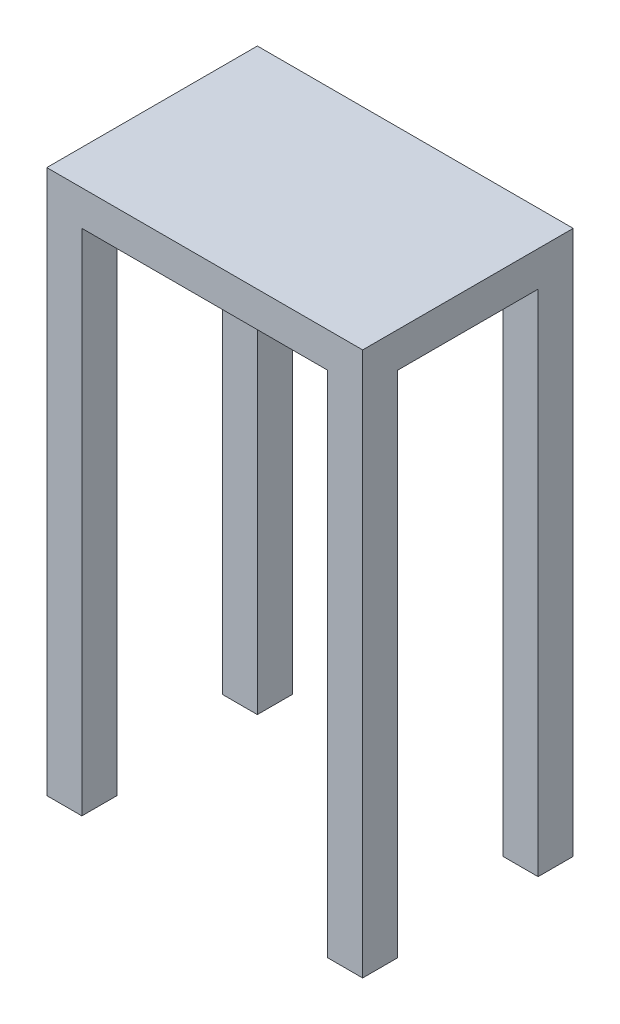
SolidWorks part; units mm, degrees
ref_plane "Front Plane" through (0, 0, 0) normal (0, 0, 1) x (1, 0, 0)
ref_plane "Top Plane" through (0, 0, 0) normal (0, 1, 0) x (1, 0, 0)
ref_plane "Right Plane" through (0, 0, 0) normal (1, 0, 0) x (0, 0, -1)
sketch "Sketch1" plane through (0, 0, 0) normal (0, 1, 0) x (1, 0, 0)
  line L1 (45, -30) -> (-45, -30)
  line L2 (45, -30) -> (45, 30)
  line L3 (45, 30) -> (-45, 30)
  line L4 (-45, -30) -> (-45, 30)
  line L5 (45, -30) -> (-45, 30) construction
  line L6 (45, 30) -> (-45, -30) construction
  point P0 (0, 0)
  dimension "D1" = 60
  dimension "D2" = 90
extrude "Boss-Extrude1" add sketch "Sketch1" along normal blind 10
sketch "Sketch2" plane through (0, 0, 0) normal (0, -1, 0) x (1, 0, 0)
  line L5 (45, -30) -> (-45, 30) construction
  line L6 (45, 30) -> (-45, -30) construction
  line L11 (-45, 30) -> (-35, 30)
  line L12 (-45, 30) -> (-45, 20)
  line L13 (-45, 20) -> (-35, 20)
  line L14 (-35, 30) -> (-35, 20)
  line L15 (-45, -30) -> (-35, -30)
  line L16 (-45, -30) -> (-45, -20)
  line L17 (-45, -20) -> (-35, -20)
  line L18 (-35, -30) -> (-35, -20)
  line L19 (35, -20) -> (45, -20)
  line L20 (35, -20) -> (35, -30)
  line L21 (35, -30) -> (45, -30)
  line L22 (45, -20) -> (45, -30)
  line L23 (35, 20) -> (45, 20)
  line L24 (35, 20) -> (35, 30)
  line L25 (35, 30) -> (45, 30)
  line L26 (45, 20) -> (45, 30)
  point P0 (0, 0)
extrude "Boss-Extrude2" add sketch "Sketch2" along normal blind 145
sketch "Sketch3" plane through (0, 0, 30) normal (0, 0, 1) x (1, 0, 0)
  line L0 (-45, 10) -> (45, 10) construction
  line L1 (-45, 10) -> (45, 10)
  line L2 (-45, 10) -> (-45, -145)
  line L3 (-45, -145) -> (45, -145)
  line L4 (45, 10) -> (45, -145)
  dimension "D1" = 155
